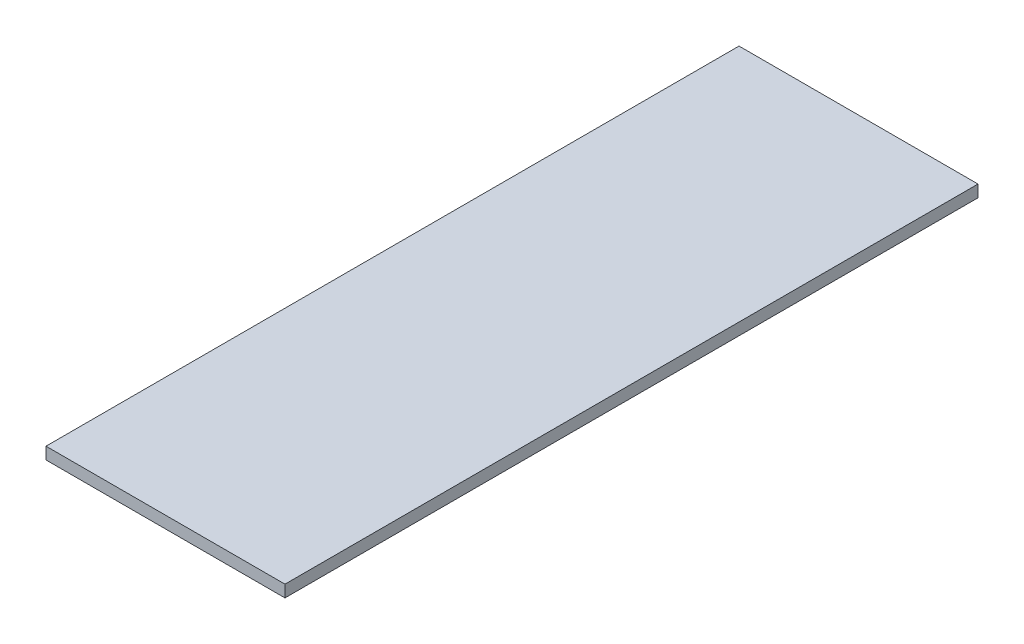
SolidWorks part; units mm, degrees
ref_plane "Plan de face" through (0, 0, 0) normal (0, 0, 1) x (1, 0, 0)
ref_plane "Plan de dessus" through (0, 0, 0) normal (0, 1, 0) x (1, 0, 0)
ref_plane "Plan de droite" through (0, 0, 0) normal (1, 0, 0) x (0, 0, -1)
sketch "Esquisse1" plane through (0, 0, 0) normal (0, 1, 0) x (1, 0, 0)
  line L1 (0, 0) -> (200, 0)
  line L2 (0, 0) -> (0, 580)
  line L3 (0, 580) -> (200, 580)
  line L4 (200, 0) -> (200, 580)
  dimension "D1" = 200
  dimension "D2" = 580
extrude "Boss.-Extru.1" add sketch "Esquisse1" along normal blind 10
